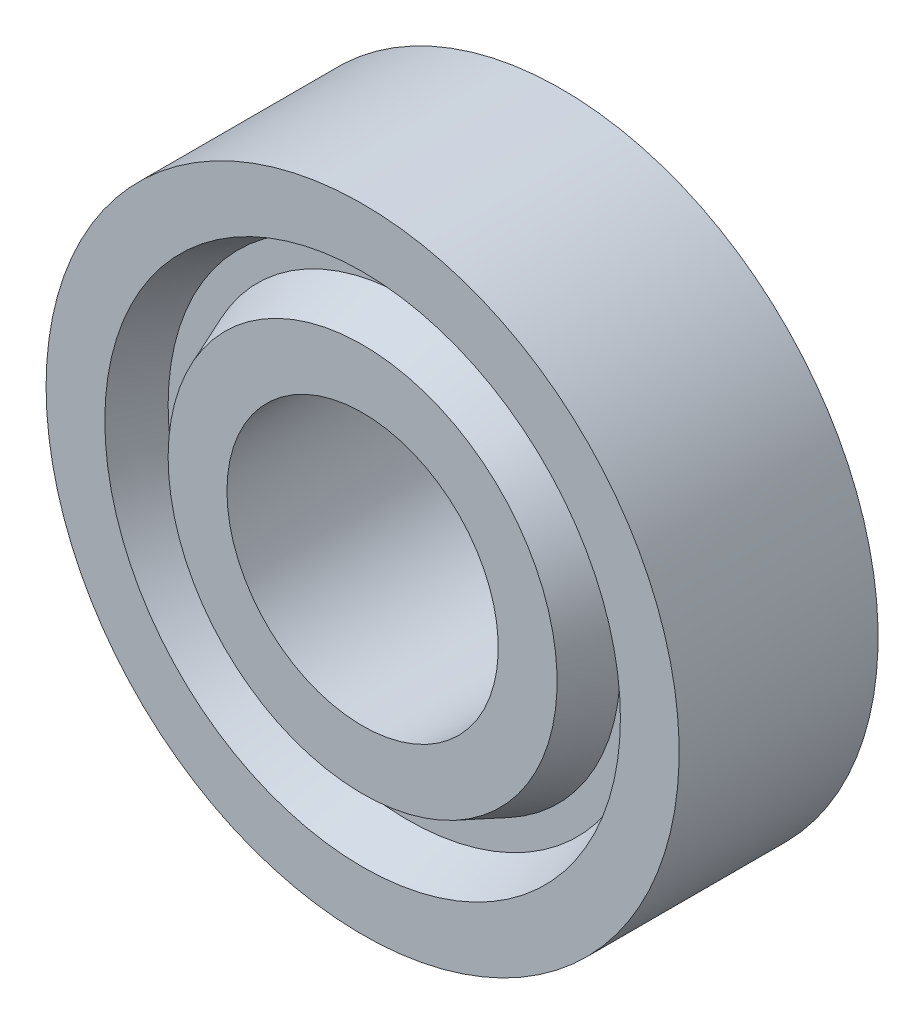
SolidWorks part; units mm, degrees
ref_plane "Front Plane" through (0, 0, 0) normal (0, 0, 1) x (1, 0, 0)
ref_plane "Top Plane" through (0, 0, 0) normal (0, 1, 0) x (1, 0, 0)
ref_plane "Right Plane" through (0, 0, 0) normal (1, 0, 0) x (0, 0, -1)
sketch "Sketch1" plane through (0, 0, 0) normal (0, 1, 0) x (1, 0, 0)
  line L0 (0, 28.9111) -> (0, -36.6207) construction
  line L2 (10.753, 5.5) -> (11.753, 3)
  line L3 (11.753, 3) -> (13.253, 3)
  line L4 (13.253, 3) -> (14.253, 5.5)
  line L6 (17.5, 5.5) -> (17.5, -5.5)
  line L8 (14.253, -5.5) -> (13.253, -3)
  line L9 (13.253, -3) -> (11.753, -3)
  line L10 (11.753, -3) -> (10.753, -5.5)
  line L12 (7.5, -5.5) -> (7.5, 5.5)
  line L13 (0, 0) -> (7.5, 0) construction
  line L14 (11.753, -3) -> (11.753, 3) construction
  line L15 (13.253, -3) -> (13.253, 3) construction
  line L16 (7.5, 5.5) -> (10.753, 5.5)
  line L17 (14.253, 5.5) -> (17.5, 5.5)
  line L18 (14.253, -5.5) -> (17.5, -5.5)
  line L19 (7.5, -5.5) -> (10.753, -5.5)
  line L20 (10.753, -5.5) -> (14.253, -5.5) construction
  line L21 (10.753, 5.5) -> (14.253, 5.5) construction
  line L22 (10.753, -5.5) -> (10.753, 5.5) construction
  line L23 (14.253, -5.5) -> (14.253, 5.5) construction
  dimension "D1" = 7.5
  dimension "D2" = 17.5
  dimension "D3" = 3.5
  dimension "D4" = 3.253
  dimension "D5" = 2.5
  dimension "D6" = 11
  dimension "D7" = 1.5
revolve "Revolve1" add sketch "Sketch1" angle 360 about L0
